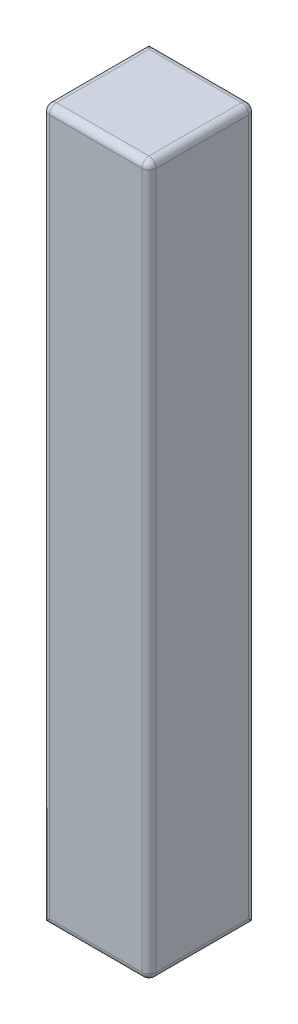
SolidWorks part; units mm, degrees
ref_plane "Front Plane" through (0, 0, 0) normal (0, 0, 1) x (1, 0, 0)
ref_plane "Top Plane" through (0, 0, 0) normal (0, 1, 0) x (1, 0, 0)
ref_plane "Right Plane" through (0, 0, 0) normal (1, 0, 0) x (0, 0, -1)
sketch "Sketch1" plane through (0, 0, 0) normal (0, 1, 0) x (1, 0, 0)
  line L1 (0, 0) -> (3, 0)
  line L2 (0, 0) -> (0, 3)
  line L3 (0, 3) -> (3, 3)
  line L4 (3, 0) -> (3, 3)
  dimension "D1" = 3
  dimension "D2" = 3
extrude "Boss-Extrude1" add sketch "Sketch1" along normal blind 20
fillet "Fillet1" radius 0.2 9 edges at (1.5, 0, 0) (3, 0, -1.5) (0, 20, -1.5) (1.5, 20, 0) (3, 20, -1.5) (1.5, 20, -3) (3, 10, -3) (3, 10, 0) (0, 10, 0)
